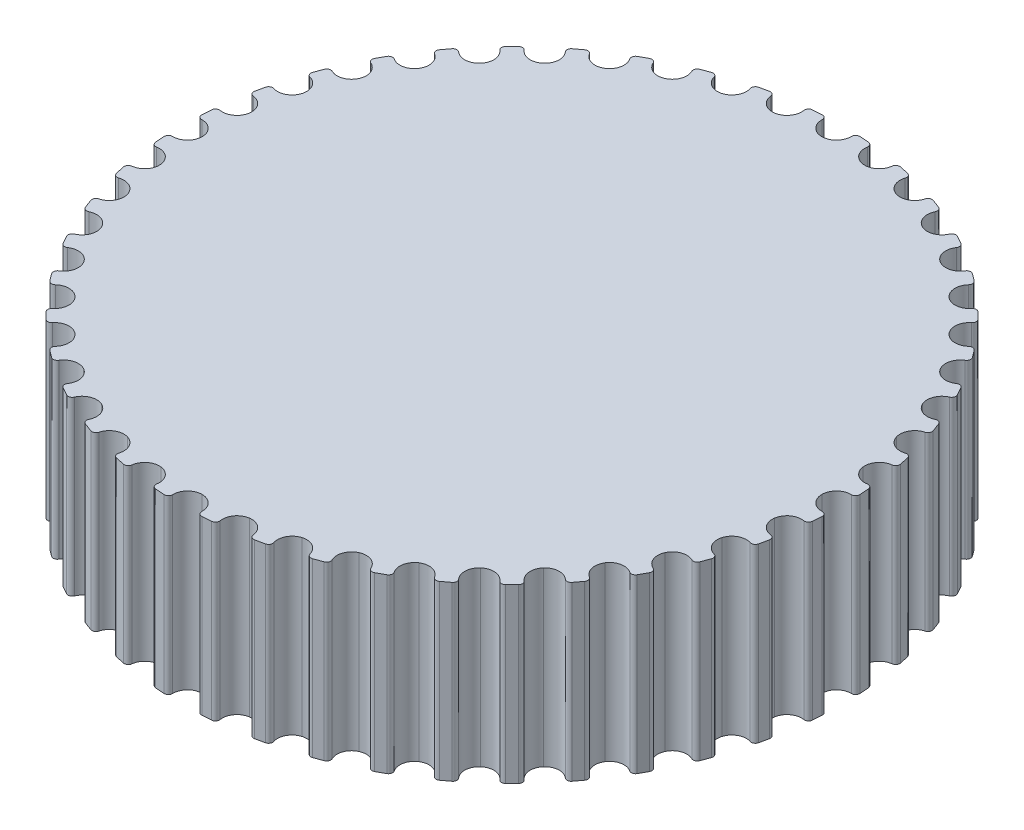
SolidWorks part; units mm, degrees
ref_plane "Ebene vorne" through (0, 0, 0) normal (0, 0, 1) x (1, 0, 0)
ref_plane "Ebene oben" through (0, 0, 0) normal (0, 1, 0) x (1, 0, 0)
ref_plane "Ebene rechts" through (0, 0, 0) normal (1, 0, 0) x (0, 0, -1)
sketch "Skizze1" plane through (0, 0, 0) normal (0, 1, 0) x (1, 0, 0)
  line L0 (0, 0) -> (0, 21118.2422) construction
  line L1 (0, 0) -> (-21118.2422, 0) construction
  line L2 (0, 0) -> (8.5282, 59.3285) construction
  line L3 (2.9279, 34.3203) -> (1.9851, 34.3877)
  line L4 (7.7814, 33.5544) -> (6.8577, 33.7553)
  line L5 (12.4765, 32.1056) -> (11.5908, 32.4359)
  line L6 (16.9176, 30.0034) -> (16.0879, 30.4564)
  line L7 (21.0143, 27.2905) -> (20.2575, 27.857)
  line L8 (24.6832, 24.0222) -> (24.0148, 24.6907)
  line L9 (27.8497, 20.2651) -> (27.2832, 21.0218)
  line L10 (30.4492, 16.0955) -> (29.9962, 16.9252)
  line L11 (32.4289, 11.5985) -> (32.0986, 12.4842)
  line L12 (33.7484, 6.8655) -> (33.5475, 7.7891)
  line L13 (34.381, 1.9928) -> (34.3135, 2.9357)
  line L14 (34.3136, -2.9202) -> (34.381, -1.9774)
  line L15 (33.5477, -7.7737) -> (33.7487, -6.85)
  line L16 (32.0989, -12.4688) -> (32.4293, -11.5831)
  line L17 (29.9967, -16.9099) -> (30.4497, -16.0802)
  line L18 (27.2839, -21.0066) -> (27.8503, -20.2498)
  line L19 (24.0156, -24.6755) -> (24.684, -24.0071)
  line L20 (20.2584, -27.842) -> (21.0152, -27.2755)
  line L21 (16.0889, -30.4415) -> (16.9185, -29.9885)
  line L22 (11.5918, -32.4212) -> (12.4775, -32.0909)
  line L23 (6.8588, -33.7408) -> (7.7825, -33.5398)
  line L24 (1.9862, -34.3733) -> (2.929, -34.3058)
  line L25 (-2.9269, -34.3059) -> (-1.984, -34.3733)
  line L26 (-7.7804, -33.54) -> (-6.8567, -33.741)
  line L27 (-12.4754, -32.0912) -> (-11.5898, -32.4216)
  line L28 (-16.9165, -29.989) -> (-16.0869, -30.442)
  line L29 (-21.0133, -27.2762) -> (-20.2565, -27.8426)
  line L30 (-24.6822, -24.0079) -> (-24.0138, -24.6763)
  line L31 (-27.8487, -20.2507) -> (-27.2822, -21.0075)
  line L32 (-30.4482, -16.0812) -> (-29.9952, -16.9108)
  line L33 (-32.4279, -11.5841) -> (-32.0975, -12.4698)
  line L34 (-33.7474, -6.8511) -> (-33.5465, -7.7748)
  line L35 (-34.38, -1.9785) -> (-34.3125, -2.9213)
  line L36 (-34.3126, 2.9346) -> (-34.38, 1.9917)
  line L37 (-33.5467, 7.7881) -> (-33.7476, 6.8644)
  line L38 (-32.0979, 12.4831) -> (-32.4282, 11.5975)
  line L39 (-29.9957, 16.9242) -> (-30.4487, 16.0946)
  line L40 (-27.2828, 21.021) -> (-27.8493, 20.2642)
  line L41 (-24.0145, 24.6899) -> (-24.683, 24.0215)
  line L42 (-20.2574, 27.8564) -> (-21.0141, 27.2899)
  line L43 (-16.0878, 30.4559) -> (-16.9175, 30.0029)
  line L44 (-11.5908, 32.4356) -> (-12.4765, 32.1052)
  line L45 (-6.8578, 33.7551) -> (-7.7814, 33.5542)
  line L46 (-1.9851, 34.3876) -> (-2.928, 34.3202)
  circle A0 centre (0, 0) radius 34.445 construction
  circle A1 centre (0, 0) radius 32.385 construction
  arc A2 (0, 32.385) -> (1.5245, 33.9481) centre (0, 33.91) ccw
  arc A3 (1.9851, 34.3877) -> (1.5245, 33.9481) centre (1.9544, 33.9588) ccw
  arc A4 (3.3212, 33.8196) -> (4.6078, 32.0555) centre (4.8248, 33.565) ccw
  arc A5 (3.3212, 33.8196) -> (2.9279, 34.3203) centre (2.8973, 33.8914) ccw
  arc A6 (4.6078, 32.0555) -> (6.3393, 33.3857) centre (4.8249, 33.565) ccw
  arc A7 (6.8577, 33.7553) -> (6.3393, 33.3857) centre (6.7663, 33.3352) ccw
  arc A8 (8.0994, 33.0028) -> (7.7814, 33.5544) centre (7.69, 33.1342) ccw
  arc A9 (8.0994, 33.0028) -> (9.1219, 31.0736) centre (9.5515, 32.5369) ccw
  arc A10 (9.1219, 31.0736) -> (11.025, 32.1439) centre (9.5515, 32.5368) ccw
  arc A11 (11.5908, 32.4359) -> (11.025, 32.1439) centre (11.4405, 32.0331) ccw
  arc A12 (12.7128, 31.5144) -> (12.4765, 32.1056) centre (12.3262, 31.7027) ccw
  arc A13 (12.7128, 31.5144) -> (13.4503, 29.4593) centre (14.0837, 30.8465) ccw
  arc A14 (13.4503, 29.4593) -> (15.4864, 30.2478) centre (14.0838, 30.8465) ccw
  arc A15 (16.0879, 30.4564) -> (15.4864, 30.2478) centre (15.8818, 30.079) ccw
  arc A16 (17.0673, 29.3846) -> (16.9176, 30.0034) centre (16.7115, 29.626) ccw
  arc A17 (17.0673, 29.3846) -> (17.5049, 27.2454) centre (18.3293, 28.5284) ccw
  arc A18 (17.5049, 27.2454) -> (19.6324, 27.7361) centre (18.3293, 28.5283) ccw
  arc A19 (20.2575, 27.857) -> (19.6324, 27.7361) centre (19.9999, 27.5128) ccw
  arc A20 (21.0745, 26.6567) -> (21.0143, 27.2905) centre (20.7566, 26.9463) ccw
  arc A21 (21.0745, 26.6567) -> (21.2031, 24.477) centre (22.2017, 25.6296) ccw
  arc A22 (21.2031, 24.477) -> (23.3788, 24.66) centre (22.2017, 25.6296) ccw
  arc A23 (24.0148, 24.6907) -> (23.3788, 24.66) centre (23.7107, 24.3866) ccw
  arc A24 (24.6526, 23.3863) -> (24.6832, 24.0222) centre (24.3792, 23.7182) ccw
  arc A25 (24.6526, 23.3863) -> (24.4697, 21.2105) centre (25.6222, 22.2092) ccw
  arc A26 (24.4697, 21.2105) -> (26.6493, 21.082) centre (25.6222, 22.2092) ccw
  arc A27 (27.2832, 21.0218) -> (26.6493, 21.082) centre (26.939, 20.7641) ccw
  arc A28 (27.7288, 19.64) -> (27.8497, 20.2651) centre (27.5055, 20.0074) ccw
  arc A29 (27.7288, 19.64) -> (27.2382, 17.5124) centre (28.5211, 18.3369) ccw
  arc A30 (27.2382, 17.5124) -> (29.3773, 17.0749) centre (28.5211, 18.3369) ccw
  arc A31 (29.9962, 16.9252) -> (29.3773, 17.0749) centre (29.6188, 16.7191) ccw
  arc A32 (30.2406, 15.494) -> (30.4492, 16.0955) centre (30.0718, 15.8895) ccw
  arc A33 (30.2406, 15.494) -> (29.4522, 13.4579) centre (30.8394, 14.0914) ccw
  arc A34 (29.4522, 13.4579) -> (31.5073, 12.7204) centre (30.8394, 14.0914) ccw
  arc A35 (32.0986, 12.4842) -> (31.5073, 12.7204) centre (31.6957, 12.3339) ccw
  arc A36 (32.1368, 11.0327) -> (32.4289, 11.5985) centre (32.026, 11.4482) ccw
  arc A37 (32.1368, 11.0327) -> (31.0667, 9.1296) centre (32.5299, 9.5593) ccw
  arc A38 (31.0667, 9.1296) -> (32.9959, 8.1072) centre (32.5299, 9.5592) ccw
  arc A39 (33.5475, 7.7891) -> (32.9959, 8.1072) centre (33.1273, 7.6977) ccw
  arc A40 (33.3788, 6.347) -> (33.7484, 6.8655) centre (33.3283, 6.7741) ccw
  arc A41 (33.3788, 6.347) -> (32.0487, 4.6155) centre (33.5582, 4.8326) ccw
  arc A42 (32.0487, 4.6155) -> (33.8128, 3.329) centre (33.5582, 4.8326) ccw
  arc A43 (34.3135, 2.9357) -> (33.8128, 3.329) centre (33.8846, 2.905) ccw
  arc A44 (33.9414, 1.5323) -> (34.381, 1.9928) centre (33.9521, 1.9621) ccw
  arc A45 (33.9414, 1.5323) -> (32.3783, 0.0077) centre (33.9033, 0.0077) ccw
  arc A46 (32.3783, 0.0077) -> (33.9414, -1.5168) centre (33.9033, 0.0077) ccw
  arc A47 (34.381, -1.9774) -> (33.9414, -1.5168) centre (33.9521, -1.9467) ccw
  arc A48 (33.8129, -3.3135) -> (34.3136, -2.9202) centre (33.8847, -2.8896) ccw
  arc A49 (33.8129, -3.3135) -> (32.0488, -4.6002) centre (33.5583, -4.8171) ccw
  arc A50 (32.0488, -4.6002) -> (33.379, -6.3316) centre (33.5583, -4.8172) ccw
  arc A51 (33.7487, -6.85) -> (33.379, -6.3316) centre (33.3285, -6.7586) ccw
  arc A52 (32.9962, -8.0917) -> (33.5477, -7.7737) centre (33.1276, -7.6823) ccw
  arc A53 (32.9962, -8.0917) -> (31.0669, -9.1142) centre (32.5302, -9.5438) ccw
  arc A54 (31.0669, -9.1142) -> (32.1372, -11.0173) centre (32.5302, -9.5438) ccw
  arc A55 (32.4293, -11.5831) -> (32.1372, -11.0173) centre (32.0264, -11.4328) ccw
  arc A56 (31.5077, -12.7051) -> (32.0989, -12.4688) centre (31.6961, -12.3185) ccw
  arc A57 (31.5077, -12.7051) -> (29.4526, -13.4426) centre (30.8398, -14.076) ccw
  arc A58 (29.4526, -13.4426) -> (30.2411, -15.4787) centre (30.8398, -14.0761) ccw
  arc A59 (30.4497, -16.0802) -> (30.2411, -15.4787) centre (30.0723, -15.8741) ccw
  arc A60 (29.3779, -17.0596) -> (29.9967, -16.9099) centre (29.6193, -16.7038) ccw
  arc A61 (29.3779, -17.0596) -> (27.2387, -17.4972) centre (28.5217, -18.3216) ccw
  arc A62 (27.2387, -17.4972) -> (27.7295, -19.6247) centre (28.5217, -18.3216) ccw
  arc A63 (27.8503, -20.2498) -> (27.7295, -19.6247) centre (27.5061, -19.9922) ccw
  arc A64 (26.65, -21.0668) -> (27.2839, -21.0066) centre (26.9396, -20.7489) ccw
  arc A65 (26.65, -21.0668) -> (24.4704, -21.1954) centre (25.6229, -22.194) ccw
  arc A66 (24.4704, -21.1954) -> (24.6533, -23.3711) centre (25.6229, -22.194) ccw
  arc A67 (24.684, -24.0071) -> (24.6533, -23.3711) centre (24.3799, -23.703) ccw
  arc A68 (23.3796, -24.6449) -> (24.0156, -24.6755) centre (23.7115, -24.3715) ccw
  arc A69 (23.3796, -24.6449) -> (21.2039, -24.462) centre (22.2026, -25.6145) ccw
  arc A70 (21.2039, -24.462) -> (21.0753, -26.6416) centre (22.2025, -25.6145) ccw
  arc A71 (21.0152, -27.2755) -> (21.0753, -26.6416) centre (20.7575, -26.9313) ccw
  arc A72 (19.6333, -27.7211) -> (20.2584, -27.842) centre (20.0007, -27.4978) ccw
  arc A73 (19.6333, -27.7211) -> (17.5057, -27.2305) centre (18.3302, -28.5134) ccw
  arc A74 (17.5057, -27.2305) -> (17.0683, -29.3696) centre (18.3302, -28.5134) ccw
  arc A75 (16.9185, -29.9885) -> (17.0683, -29.3696) centre (16.7124, -29.6111) ccw
  arc A76 (15.4873, -30.2329) -> (16.0889, -30.4415) centre (15.8828, -30.0641) ccw
  arc A77 (15.4873, -30.2329) -> (13.4512, -29.4445) centre (14.0848, -30.8317) ccw
  arc A78 (13.4512, -29.4445) -> (12.7138, -31.4996) centre (14.0847, -30.8317) ccw
  arc A79 (12.4775, -32.0909) -> (12.7138, -31.4996) centre (12.3272, -31.688) ccw
  arc A80 (11.0261, -32.1291) -> (11.5918, -32.4212) centre (11.4415, -32.0183) ccw
  arc A81 (11.0261, -32.1291) -> (9.1229, -31.059) centre (9.5526, -32.5222) ccw
  arc A82 (9.1229, -31.059) -> (8.1005, -32.9882) centre (9.5525, -32.5222) ccw
  arc A83 (7.7825, -33.5398) -> (8.1005, -32.9882) centre (7.6911, -33.1196) ccw
  arc A84 (6.3404, -33.3711) -> (6.8588, -33.7408) centre (6.7674, -33.3206) ccw
  arc A85 (6.3404, -33.3711) -> (4.6089, -32.041) centre (4.8259, -33.5505) ccw
  arc A86 (4.6089, -32.041) -> (3.3223, -33.8051) centre (4.8259, -33.5505) ccw
  arc A87 (2.929, -34.3058) -> (3.3223, -33.8051) centre (2.8983, -33.8769) ccw
  arc A88 (1.5256, -33.9337) -> (1.9862, -34.3733) centre (1.9555, -33.9444) ccw
  arc A89 (1.5256, -33.9337) -> (0.001, -32.3706) centre (0.0011, -33.8956) ccw
  arc A90 (0.001, -32.3706) -> (-1.5235, -33.9337) centre (0.001, -33.8956) ccw
  arc A91 (-1.984, -34.3733) -> (-1.5235, -33.9337) centre (-1.9534, -33.9444) ccw
  arc A92 (-3.3202, -33.8052) -> (-2.9269, -34.3059) centre (-2.8962, -33.877) ccw
  arc A93 (-3.3202, -33.8052) -> (-4.6068, -32.0411) centre (-4.8238, -33.5506) ccw
  arc A94 (-4.6068, -32.0411) -> (-6.3383, -33.3713) centre (-4.8239, -33.5506) ccw
  arc A95 (-6.8567, -33.741) -> (-6.3383, -33.3713) centre (-6.7653, -33.3208) ccw
  arc A96 (-8.0984, -32.9885) -> (-7.7804, -33.54) centre (-7.689, -33.1199) ccw
  arc A97 (-8.0984, -32.9885) -> (-9.1209, -31.0592) centre (-9.5505, -32.5225) ccw
  arc A98 (-9.1209, -31.0592) -> (-11.024, -32.1295) centre (-9.5505, -32.5225) ccw
  arc A99 (-11.5898, -32.4216) -> (-11.024, -32.1295) centre (-11.4395, -32.0187) ccw
  arc A100 (-12.7118, -31.5) -> (-12.4754, -32.0912) centre (-12.3252, -31.6884) ccw
  arc A101 (-12.7118, -31.5) -> (-13.4492, -29.4449) centre (-14.0827, -30.8321) ccw
  arc A102 (-13.4492, -29.4449) -> (-15.4853, -30.2334) centre (-14.0828, -30.8321) ccw
  arc A103 (-16.0869, -30.442) -> (-15.4853, -30.2334) centre (-15.8808, -30.0646) ccw
  arc A104 (-17.0663, -29.3702) -> (-16.9165, -29.989) centre (-16.7105, -29.6116) ccw
  arc A105 (-17.0663, -29.3702) -> (-17.5038, -27.231) centre (-18.3283, -28.514) ccw
  arc A106 (-17.5038, -27.231) -> (-19.6314, -27.7218) centre (-18.3283, -28.514) ccw
  arc A107 (-20.2565, -27.8426) -> (-19.6314, -27.7218) centre (-19.9988, -27.4984) ccw
  arc A108 (-21.0734, -26.6423) -> (-21.0133, -27.2762) centre (-20.7556, -26.9319) ccw
  arc A109 (-21.0734, -26.6423) -> (-21.2021, -24.4627) centre (-22.2007, -25.6152) ccw
  arc A110 (-21.2021, -24.4627) -> (-23.3778, -24.6456) centre (-22.2007, -25.6152) ccw
  arc A111 (-24.0138, -24.6763) -> (-23.3778, -24.6456) centre (-23.7097, -24.3722) ccw
  arc A112 (-24.6515, -23.3719) -> (-24.6822, -24.0079) centre (-24.3781, -23.7038) ccw
  arc A113 (-24.6515, -23.3719) -> (-24.4687, -21.1962) centre (-25.6212, -22.1949) ccw
  arc A114 (-24.4687, -21.1962) -> (-26.6483, -21.0676) centre (-25.6212, -22.1948) ccw
  arc A115 (-27.2822, -21.0075) -> (-26.6483, -21.0676) centre (-26.9379, -20.7498) ccw
  arc A116 (-27.7278, -19.6256) -> (-27.8487, -20.2507) centre (-27.5044, -19.993) ccw
  arc A117 (-27.7278, -19.6256) -> (-27.2372, -17.498) centre (-28.52, -18.3225) ccw
  arc A118 (-27.2372, -17.498) -> (-29.3763, -17.0606) centre (-28.5201, -18.3225) ccw
  arc A119 (-29.9952, -16.9108) -> (-29.3763, -17.0606) centre (-29.6178, -16.7047) ccw
  arc A120 (-30.2396, -15.4796) -> (-30.4482, -16.0812) centre (-30.0708, -15.8751) ccw
  arc A121 (-30.2396, -15.4796) -> (-29.4512, -13.4435) centre (-30.8383, -14.0771) ccw
  arc A122 (-29.4512, -13.4435) -> (-31.5063, -12.7061) centre (-30.8384, -14.077) ccw
  arc A123 (-32.0975, -12.4698) -> (-31.5063, -12.7061) centre (-31.6946, -12.3195) ccw
  arc A124 (-32.1358, -11.0184) -> (-32.4279, -11.5841) centre (-32.025, -11.4338) ccw
  arc A125 (-32.1358, -11.0184) -> (-31.0656, -9.1152) centre (-32.5288, -9.5449) ccw
  arc A126 (-31.0656, -9.1152) -> (-32.9949, -8.0928) centre (-32.5289, -9.5448) ccw
  arc A127 (-33.5465, -7.7748) -> (-32.9949, -8.0928) centre (-33.1263, -7.6834) ccw
  arc A128 (-33.3778, -6.3327) -> (-33.7474, -6.8511) centre (-33.3273, -6.7597) ccw
  arc A129 (-33.3778, -6.3327) -> (-32.0477, -4.6012) centre (-33.5571, -4.8182) ccw
  arc A130 (-32.0477, -4.6012) -> (-33.8118, -3.3146) centre (-33.5571, -4.8182) ccw
  arc A131 (-34.3125, -2.9213) -> (-33.8118, -3.3146) centre (-33.8836, -2.8906) ccw
  arc A132 (-33.9403, -1.5179) -> (-34.38, -1.9785) centre (-33.951, -1.9478) ccw
  arc A133 (-33.9403, -1.5179) -> (-32.3773, 0.0067) centre (-33.9023, 0.0066) ccw
  arc A134 (-32.3773, 0.0067) -> (-33.9404, 1.5312) centre (-33.9023, 0.0067) ccw
  arc A135 (-34.38, 1.9917) -> (-33.9404, 1.5312) centre (-33.9511, 1.9611) ccw
  arc A136 (-33.8119, 3.3279) -> (-34.3126, 2.9346) centre (-33.8837, 2.9039) ccw
  arc A137 (-33.8119, 3.3279) -> (-32.0478, 4.6145) centre (-33.5573, 4.8315) ccw
  arc A138 (-32.0478, 4.6145) -> (-33.378, 6.346) centre (-33.5573, 4.8315) ccw
  arc A139 (-33.7476, 6.8644) -> (-33.378, 6.346) centre (-33.3275, 6.773) ccw
  arc A140 (-32.9951, 8.1061) -> (-33.5467, 7.7881) centre (-33.1265, 7.6967) ccw
  arc A141 (-32.9951, 8.1061) -> (-31.0659, 9.1286) centre (-32.5292, 9.5582) ccw
  arc A142 (-31.0659, 9.1286) -> (-32.1362, 11.0317) centre (-32.5291, 9.5582) ccw
  arc A143 (-32.4282, 11.5975) -> (-32.1362, 11.0317) centre (-32.0254, 11.4472) ccw
  arc A144 (-31.5067, 12.7194) -> (-32.0979, 12.4831) centre (-31.695, 12.3329) ccw
  arc A145 (-31.5067, 12.7194) -> (-29.4516, 13.4569) centre (-30.8388, 14.0904) ccw
  arc A146 (-29.4516, 13.4569) -> (-30.2401, 15.493) centre (-30.8388, 14.0905) ccw
  arc A147 (-30.4487, 16.0946) -> (-30.2401, 15.493) centre (-30.0713, 15.8885) ccw
  arc A148 (-29.3769, 17.074) -> (-29.9957, 16.9242) centre (-29.6183, 16.7182) ccw
  arc A149 (-29.3769, 17.074) -> (-27.2377, 17.5115) centre (-28.5207, 18.336) ccw
  arc A150 (-27.2377, 17.5115) -> (-27.7284, 19.6391) centre (-28.5206, 18.336) ccw
  arc A151 (-27.8493, 20.2642) -> (-27.7284, 19.6391) centre (-27.5051, 20.0065) ccw
  arc A152 (-26.649, 21.0811) -> (-27.2828, 21.021) centre (-26.9386, 20.7633) ccw
  arc A153 (-26.649, 21.0811) -> (-24.4693, 21.2098) centre (-25.6219, 22.2084) ccw
  arc A154 (-24.4693, 21.2098) -> (-24.6523, 23.3855) centre (-25.6219, 22.2084) ccw
  arc A155 (-24.683, 24.0215) -> (-24.6523, 23.3855) centre (-24.3789, 23.7174) ccw
  arc A156 (-23.3786, 24.6592) -> (-24.0145, 24.6899) centre (-23.7105, 24.3858) ccw
  arc A157 (-23.3786, 24.6592) -> (-21.2028, 24.4764) centre (-22.2015, 25.6289) ccw
  arc A158 (-21.2028, 24.4764) -> (-21.0743, 26.656) centre (-22.2015, 25.6289) ccw
  arc A159 (-21.0141, 27.2899) -> (-21.0743, 26.656) centre (-20.7564, 26.9456) ccw
  arc A160 (-19.6323, 27.7355) -> (-20.2574, 27.8564) centre (-19.9997, 27.5121) ccw
  arc A161 (-19.6323, 27.7355) -> (-17.5047, 27.2449) centre (-18.3292, 28.5277) ccw
  arc A162 (-17.5047, 27.2449) -> (-17.0672, 29.384) centre (-18.3292, 28.5278) ccw
  arc A163 (-16.9175, 30.0029) -> (-17.0672, 29.384) centre (-16.7114, 29.6255) ccw
  arc A164 (-15.4863, 30.2473) -> (-16.0878, 30.4559) centre (-15.8818, 30.0785) ccw
  arc A165 (-15.4863, 30.2473) -> (-13.4502, 29.4589) centre (-14.0837, 30.846) ccw
  arc A166 (-13.4502, 29.4589) -> (-12.7128, 31.514) centre (-14.0837, 30.8461) ccw
  arc A167 (-12.4765, 32.1052) -> (-12.7128, 31.514) centre (-12.3262, 31.7023) ccw
  arc A168 (-11.025, 32.1435) -> (-11.5908, 32.4356) centre (-11.4405, 32.0327) ccw
  arc A169 (-11.025, 32.1435) -> (-9.1219, 31.0733) centre (-9.5516, 32.5365) ccw
  arc A170 (-9.1219, 31.0733) -> (-8.0995, 33.0026) centre (-9.5515, 32.5366) ccw
  arc A171 (-7.7814, 33.5542) -> (-8.0995, 33.0026) centre (-7.69, 33.134) ccw
  arc A172 (-6.3393, 33.3855) -> (-6.8578, 33.7551) centre (-6.7664, 33.3349) ccw
  arc A173 (-6.3393, 33.3855) -> (-4.6078, 32.0554) centre (-4.8249, 33.5648) ccw
  arc A174 (-4.6078, 32.0554) -> (-3.3213, 33.8195) centre (-4.8249, 33.5648) ccw
  arc A175 (-2.928, 34.3202) -> (-3.3213, 33.8195) centre (-2.8973, 33.8913) ccw
  arc A176 (-1.5246, 33.948) -> (-1.9851, 34.3876) centre (-1.9544, 33.9587) ccw
  arc A177 (-1.5246, 33.948) -> (0, 32.385) centre (0, 33.91) ccw
  point P9 (4.6079, 32.0555)
  point P452 (0.0005, 0.0072)
  dimension "D1" = 68.89
  dimension "D2" = 64.77
  dimension "D3" = 3.05
  dimension "D5" = 0.86
  dimension "D4" = 8.18
  dimension "D6" = 44
extrude "Aufsatz-Linear austragen1" add sketch "Skizze1" along normal blind 18
